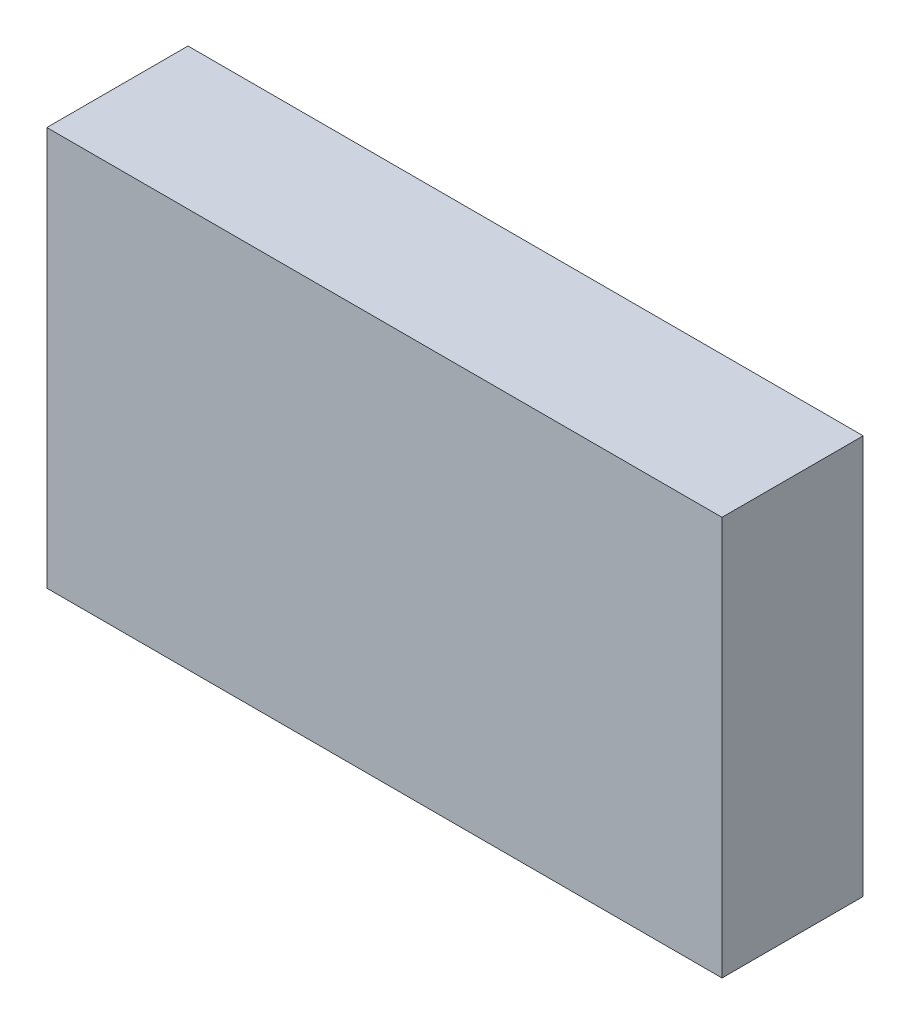
SolidWorks part; units mm, degrees
ref_plane "Front Plane" through (0, 0, 0) normal (0, 0, 1) x (1, 0, 0)
ref_plane "Top Plane" through (0, 0, 0) normal (0, 1, 0) x (1, 0, 0)
ref_plane "Right Plane" through (0, 0, 0) normal (1, 0, 0) x (0, 0, -1)
sketch "Sketch2" plane through (0, 0, 0) normal (0, 0, 1) x (1, 0, 0)
  line L1 (0, 0) -> (110, 0)
  line L2 (0, 0) -> (0, 65)
  line L3 (0, 65) -> (110, 65)
  line L4 (110, 0) -> (110, 65)
  dimension "D1" = 110
  dimension "D2" = 65
extrude "Boss-Extrude1" add sketch "Sketch2" along normal blind 23
